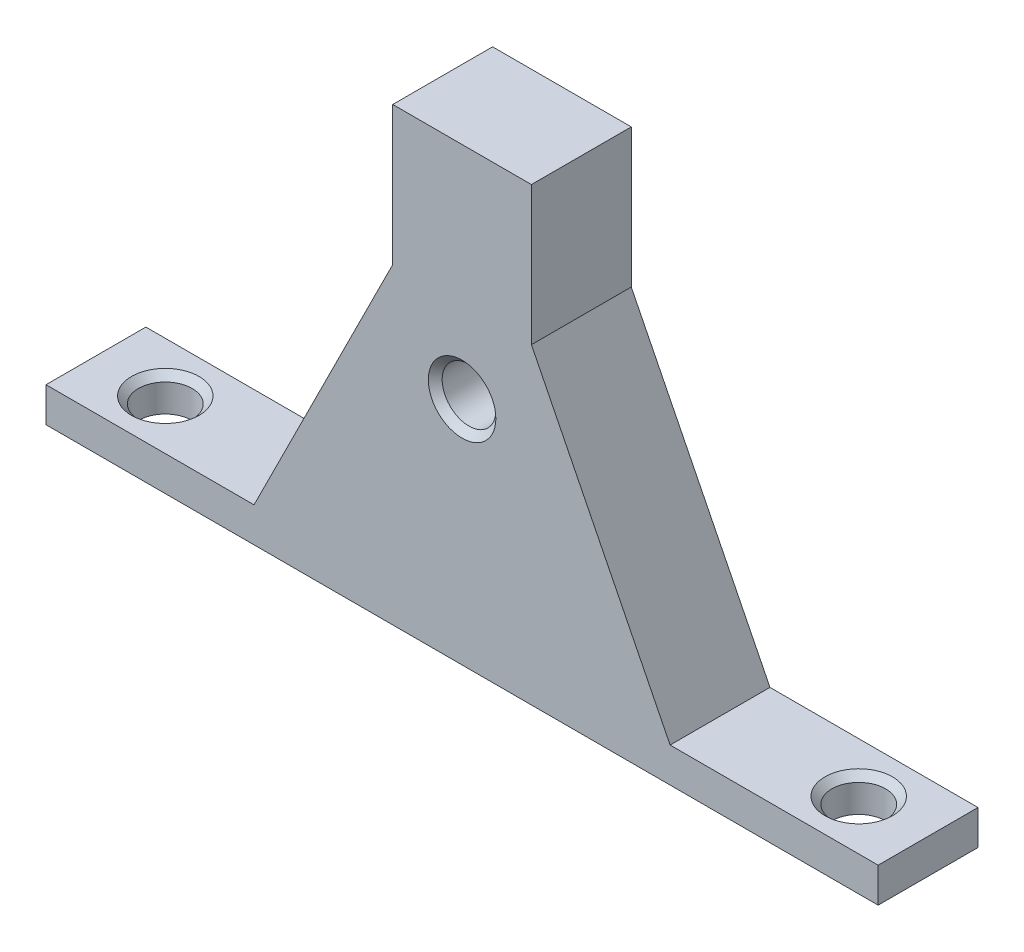
SolidWorks part; units mm, degrees
ref_plane "Front Plane" through (0, 0, 0) normal (0, 0, 1) x (1, 0, 0)
ref_plane "Top Plane" through (0, 0, 0) normal (0, 1, 0) x (1, 0, 0)
ref_plane "Right Plane" through (0, 0, 0) normal (1, 0, 0) x (0, 0, -1)
sketch "Sketch1" plane through (0, 0, 0) normal (0, 1, 0) x (1, 0, 0)
  line L1 (-38.1, -4.572) -> (38.1, -4.572)
  line L2 (-38.1, -4.572) -> (-38.1, 4.572)
  line L3 (-38.1, 4.572) -> (38.1, 4.572)
  line L4 (38.1, -4.572) -> (38.1, 4.572)
  line L5 (-38.1, -4.572) -> (38.1, 4.572) construction
  line L6 (-38.1, 4.572) -> (38.1, -4.572) construction
  point P0 (0, 0)
  dimension "D1" = 76.2
  dimension "D2" = 9.144
extrude "Boss-Extrude1" add sketch "Sketch1" along normal blind 3.175
hole_wizard "#8 Clearance Hole1" positions "Sketch2" profile "Sketch3" hole size "#8" standard "ANSI Inch" end condition through all
sketch "Sketch2" plane through (0, 3.175, 0) normal (0, 1, 0) x (1, 0, 0)
  point P0 (-31.75, 0)
  point P2 (31.75, 0)
  dimension "D1" = 31.75
  dimension "D2" = 31.75
sketch "Sketch3" plane through (-31.75, 3.175, 0) normal (1, 0, 0) x (0, 0, 1)
  line L0 (0, 0) -> (0, 3.175)
  line L1 (0, 3.175) -> (2.4574, 3.175)
  line L2 (2.4574, 3.175) -> (2.4574, 0.635)
  line L3 (2.4574, 0.635) -> (3.0924, 0)
  line L5 (3.0924, 0) -> (0, 0)
  line L6 (-2.4574, 0.635) -> (-3.0924, 0) construction
  line L11 (0, -6.35) -> (0, 107.95) construction
  dimension "Thru Hole Dia." = 4.9149
  dimension "Thru Hole Depth" = 3.175
  dimension "Near C'Sink Dia." = 6.1849
  dimension "Near C'Sink Angle" = 90
sketch "Sketch4" plane through (0, 0, 4.572) normal (0, 0, 1) x (1, 0, 0)
  line L0 (-19.05, 3.175) -> (-6.35, 28.575)
  line L1 (-6.35, 28.575) -> (-6.35, 41.275)
  line L2 (-6.35, 41.275) -> (6.35, 41.275)
  line L3 (0, 41.275) -> (0, 3.175)
  line L4 (-38.1, 0) -> (38.1, 0)
  line L5 (38.1, 0) -> (38.1, 3.175)
  line L6 (38.1, 3.175) -> (-38.1, 3.175)
  line L7 (-38.1, 3.175) -> (-38.1, 0)
  line L8 (-38.1, 0) -> (38.1, 0)
  line L9 (38.1, 0) -> (38.1, 3.175)
  line L10 (38.1, 3.175) -> (-38.1, 3.175)
  line L11 (-38.1, 3.175) -> (-38.1, 0)
  line L12 (0, 3.175) -> (-19.05, 3.175)
  line L13 (6.35, 28.575) -> (6.35, 41.275)
  line L14 (19.05, 3.175) -> (6.35, 28.575)
  line M10 (38.1, 3.175) -> (-38.1, 3.175)
  dimension "D2" = 38.1
  dimension "D3" = 6.35
  dimension "D4" = 19.05
  dimension "D5" = 12.7
  dimension "D1" = 0
extrude "Boss-Extrude2" add sketch "Sketch4" against normal up to surface (9.144 mm away) contours L3 L2 L1 L0 M10 | L10 L14 L13 L2 L3 up to face at (0, 1.5875, -4.572)
hole_wizard "#8 Clearance Hole2" positions "Sketch5" profile "Sketch6" hole size "#8" standard "ANSI Inch" end condition through all
sketch "Sketch5" plane through (0, 0, 4.572) normal (0, 0, 1) x (1, 0, 0)
  line L0 (-6.35, 41.275) -> (6.35, 41.275) construction
  point P0 (0, 21.082)
  dimension "D1" = 20.193
sketch "Sketch6" plane through (0, 21.082, 4.572) normal (1, 0, 0) x (0, -1, 0)
  line L0 (0, 0) -> (0, 9.144)
  line L1 (0, 9.144) -> (2.4574, 9.144)
  line L2 (2.4574, 9.144) -> (2.4574, 0.635)
  line L3 (2.4574, 0.635) -> (3.0924, 0)
  line L5 (3.0924, 0) -> (0, 0)
  line L6 (-2.4574, 0.635) -> (-3.0924, 0) construction
  line L11 (0, -6.35) -> (0, 107.95) construction
  dimension "Thru Hole Dia." = 4.9149
  dimension "Thru Hole Depth" = 9.144
  dimension "Near C'Sink Dia." = 6.1849
  dimension "Near C'Sink Angle" = 90
